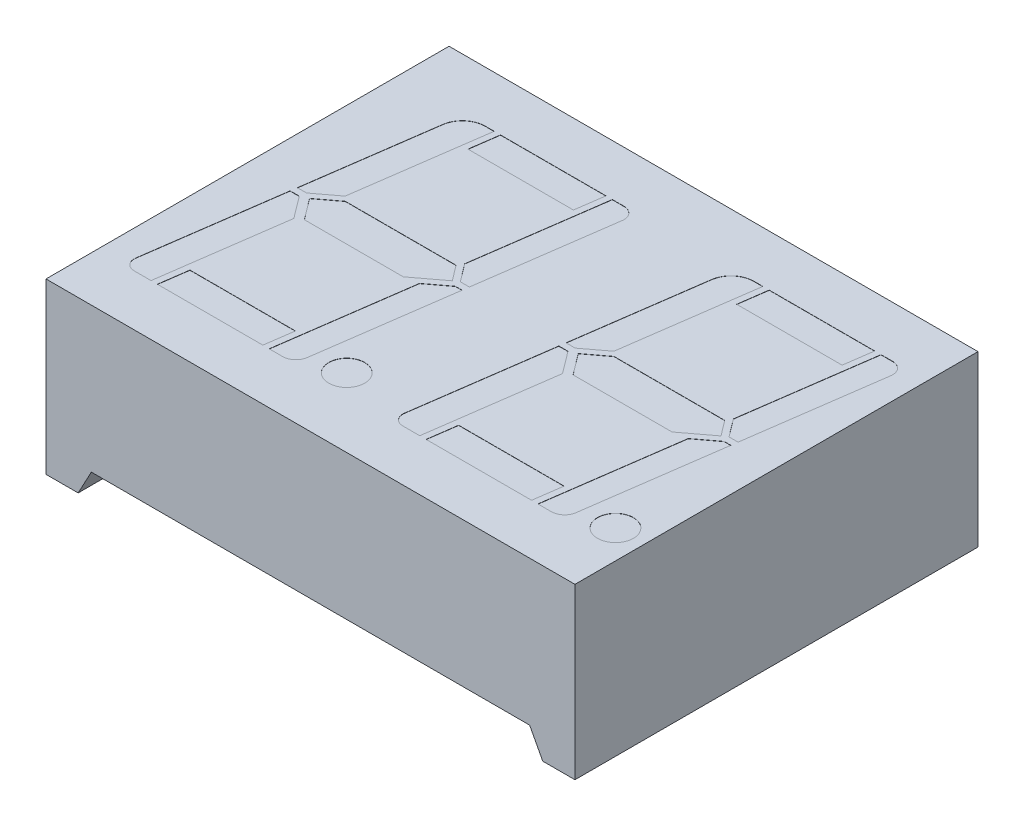
SolidWorks part; units mm, degrees
ref_plane "Front Plane" through (0, 0, 0) normal (0, 0, 1) x (1, 0, 0)
ref_plane "Top Plane" through (0, 0, 0) normal (0, 1, 0) x (1, 0, 0)
ref_plane "Right Plane" through (0, 0, 0) normal (1, 0, 0) x (0, 0, -1)
sketch "Sketch1" plane through (0, 0, 0) normal (0, 1, 0) x (1, 0, 0)
  line L1 (12.5, -9.525) -> (-12.5, -9.525)
  line L2 (12.5, -9.525) -> (12.5, 9.525)
  line L3 (12.5, 9.525) -> (-12.5, 9.525)
  line L4 (-12.5, -9.525) -> (-12.5, 9.525)
  line L5 (12.5, -9.525) -> (-12.5, 9.525) construction
  line L6 (12.5, 9.525) -> (-12.5, -9.525) construction
  point P0 (0, 0)
  dimension "D1" = 19.05
  dimension "D2" = 25
extrude "Boss-Extrude1" add sketch "Sketch1" along normal blind 8
sketch "Sketch2" plane through (0, 0, 9.525) normal (0, 0, 1) x (1, 0, 0)
  line L0 (-10.9796, 0) -> (-10.3577, 1.1654)
  line L1 (-12.5, 0) -> (12.5, 0) construction
  line L2 (-10.3577, 1.1654) -> (10.3577, 1.1654)
  line L3 (0, 0) -> (0, 8) construction
  line L4 (-12.5, 8) -> (12.5, 8) construction
  line L5 (10.9796, 0) -> (10.3577, 1.1654)
  point P12 (0, 1.1654)
  dimension "D1" = 1.5204
extrude "Cut-Extrude1" cut sketch "Sketch2" along direction (0, 0, 1) on the side against the normal through all
sketch "Sketch3" plane through (0, 8, 0) normal (0, 1, 0) x (1, 0, 0)
  line L0 (0, -9.525) -> (0, 9.525) construction
  line L1 (-12.5, -9.525) -> (12.5, -9.525) construction
  line L2 (12.5, 9.525) -> (-12.5, 9.525) construction
  line L3 (0, 0) -> (-12.5, 0) construction
  line L4 (-3.1842, -7.11) -> (0, -7.11) construction
  line L5 (-12.5, 9.525) -> (-12.5, -9.525) construction
  line L6 (-10.2939, 0.15) -> (-9.4466, 6.1791)
  line L7 (-11.3142, -7.11) -> (-3.1842, -7.11) construction
  line L8 (-11.3142, -7.11) -> (-9.3158, 7.11) construction
  line L9 (-9.3158, 7.11) -> (-1.1858, 7.11) construction
  line L10 (-3.1842, -7.11) -> (-1.1858, 7.11) construction
  line L11 (-11.3142, -7.11) -> (-1.1858, 7.11) construction
  line L12 (-9.3158, 7.11) -> (-3.1842, -7.11) construction
  line L13 (-7.9525, 7.11) -> (-8.8203, 0.9351)
  line L14 (-7.9525, 7.11) -> (-8.3757, 7.11)
  line L15 (-10.2939, 0.15) -> (-9.8622, 0.15)
  line L16 (-9.8622, 0.15) -> (-8.8203, 0.9351)
  line L17 (-6.25, 0.2145) -> (-6.25, 0.8985) construction
  line L18 (-2.3672, 7.11) -> (-1.8135, 7.11)
  line L19 (-7.6525, 7.11) -> (-2.6672, 7.11)
  line L20 (-7.6525, 7.11) -> (-7.8422, 5.76)
  line L21 (-7.8422, 5.76) -> (-2.8569, 5.76)
  line L22 (-2.6672, 7.11) -> (-2.8569, 5.76)
  line L23 (-1.2731, 6.4884) -> (-2.1639, 0.15)
  line L24 (-2.3672, 7.11) -> (-3.2272, 0.9904)
  line L25 (-3.2272, 0.9904) -> (-2.5939, 0.15)
  line L26 (-2.5939, 0.15) -> (-2.1639, 0.15)
  line L27 (-8.6046, 0.7266) -> (-3.37, 0.7266)
  line L28 (-8.6046, 0.7266) -> (-9.5688, 0)
  line L29 (-3.37, 0.7266) -> (-2.8225, 0)
  line L30 (-10.3361, -0.15) -> (-9.9043, -0.15)
  line L31 (-9.9043, -0.15) -> (-9.1192, -1.1919)
  line L32 (-9.1192, -1.1919) -> (-9.951, -7.11)
  line L33 (-9.951, -7.11) -> (-10.7505, -7.11)
  line L34 (-10.3361, -0.15) -> (-11.2358, -6.5517)
  line L35 (-9.8622, 0.15) -> (-9.756, 0.9057) construction
  line L36 (-2.8225, 0) -> (-4.1425, -0.9947)
  line L37 (-9.651, -7.11) -> (-4.6657, -7.11)
  line L38 (-9.651, -7.11) -> (-9.4612, -5.76)
  line L39 (-9.4612, -5.76) -> (-4.4759, -5.76)
  line L40 (-4.6657, -7.11) -> (-4.4759, -5.76)
  line L41 (-4.1425, -0.9947) -> (-8.8192, -0.9947)
  line L42 (-8.8192, -0.9947) -> (-9.5688, 0)
  line L43 (-2.2061, -0.15) -> (-3.1083, -6.5694)
  line L44 (-3.7302, -7.11) -> (-4.3657, -7.11)
  line L45 (-4.3657, -7.11) -> (-3.4899, -0.8786)
  line L46 (-3.4899, -0.8786) -> (-2.523, -0.15)
  line L47 (-2.523, -0.15) -> (-2.2061, -0.15)
  circle A0 centre (-1.55, -6.26) radius 0.85
  arc A1 (-9.4466, 6.1791) -> (-8.3757, 7.11) centre (-8.3757, 6.0286) cw
  arc A2 (-1.8135, 7.11) -> (-1.2731, 6.4884) centre (-1.8135, 6.5643) cw
  arc A3 (-11.2358, -6.5517) -> (-10.7505, -7.11) centre (-10.7505, -6.6199) ccw
  arc A4 (-3.7302, -7.11) -> (-3.1083, -6.5694) centre (-3.7302, -6.482) ccw
  point P12 (-6.25, 0)
  dimension "D1" = 4.7
  dimension "D2" = 14.22
  dimension "D3" = 8.13
  dimension "D4" = 1.35
  dimension "D5" = 8
  dimension "D6" = 135
  dimension "D7" = 0.4318
  dimension "D8" = 0.15
  dimension "D9" = 0.3
  dimension "D10" = 1.35
  dimension "D11" = 0.15
  dimension "D12" = 0.3
  dimension "D13" = 0.43
  dimension "D14" = 135
  dimension "D15" = 0.3
  dimension "D16" = 0.3
  dimension "D17" = 135
  dimension "D18" = 1.35
  dimension "D19" = 0.3
  dimension "D20" = 0.15
  dimension "D21" = 135
  dimension "D22" = 0.3
  dimension "D23" = 0.3
  dimension "D24" = 0.15
extrude "Cut-Extrude3" cut sketch "Sketch3" against normal blind 0.01
pattern_linear "LPattern2" count 2 spacing 12.7 along (1, 0, 0) of "Cut-Extrude3"
equation "\"D2@Sketch3\" = 14.22 / 2"
equation "\"SegmentSpace\"=0.3"
equation "\"D8@Sketch3\"=\"SegmentSpace\" /2"
equation "\"D9@Sketch3\"=\"SegmentSpace\""
equation "\"SegmentWidth\"=1.35"
equation "\"D4@Sketch3\"=\"SegmentWidth\""
equation "\"D10@Sketch3\"=\"SegmentWidth\""
equation "\"D11@Sketch3\"=\"SegmentSpace\" /2"
equation "\"D12@Sketch3\"=\"SegmentSpace\""
equation "\"D15@Sketch3\"=\"SegmentSpace\""
equation "\"D16@Sketch3\"=\"SegmentSpace\""
equation "\"D18@Sketch3\"=\"SegmentWidth\""
equation "\"D19@Sketch3\"=\"SegmentSpace\""
equation "\"D20@Sketch3\"=\"SegmentSpace\" / 2"
equation "\"D22@Sketch3\"=\"SegmentSpace\""
equation "\"D23@Sketch3\"=\"SegmentSpace\""
equation "\"D24@Sketch3\"=\"SegmentSpace\" /2"
equation "\"D25@Sketch3\" = \"SegmentSpace\""
